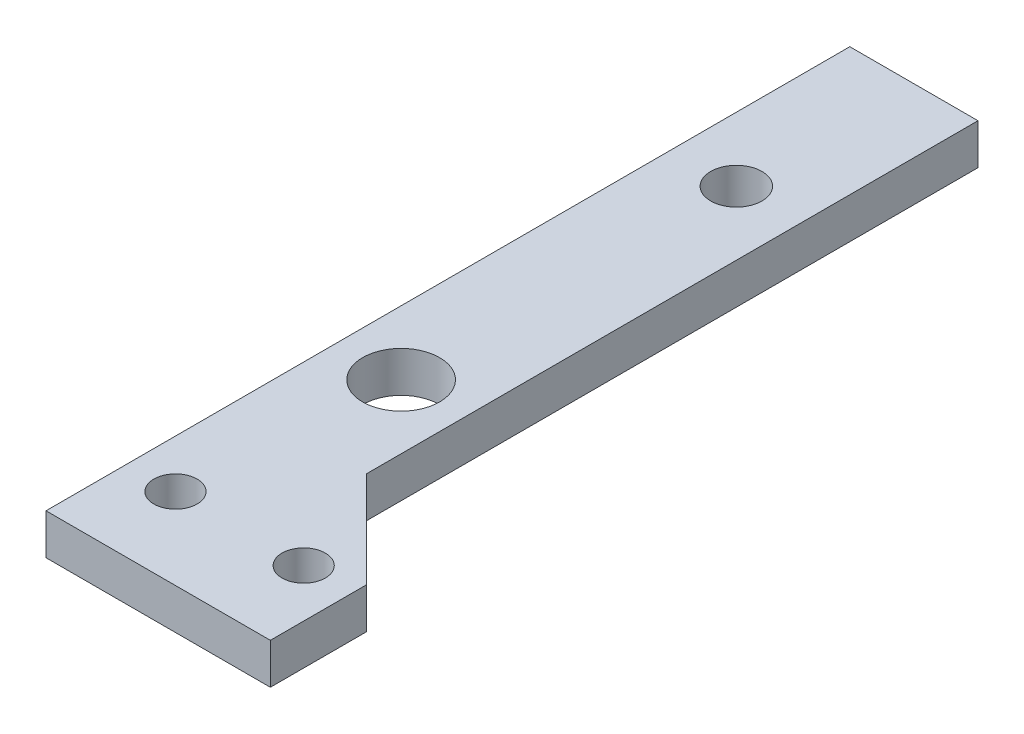
SolidWorks part; units mm, degrees
ref_plane "Front Plane" through (0, 0, 0) normal (0, 0, 1) x (1, 0, 0)
ref_plane "Top Plane" through (0, 0, 0) normal (0, 1, 0) x (1, 0, 0)
ref_plane "Right Plane" through (0, 0, 0) normal (1, 0, 0) x (0, 0, -1)
sketch "Sketch2" plane through (0, 0, 0) normal (0, 1, 0) x (1, 0, 0)
  line L0 (10, 0) -> (10, -100) construction
  line L1 (0, 0) -> (20, 0)
  line L2 (0, 0) -> (0, -100)
  line L3 (0, -100) -> (20, -100)
  line L4 (20, 0) -> (20, -100)
  circle A0 centre (10, -80) radius 6
  circle A1 centre (10, -27.7) radius 4
  dimension "D3" = 8
  dimension "D4" = 12
  dimension "D1" = 100
  dimension "D2" = 20
  dimension "D5" = 52.3
  dimension "D6" = 20
extrude "Boss-Extrude1" add sketch "Sketch2" along normal blind 6.35
sketch "Sketch4" plane through (0, 6.35, 0) normal (0, 1, 0) x (1, 0, 0)
  line L0 (0, -100) -> (20, -100) construction
  line L1 (0, -100) -> (20, -100)
  line L2 (0, -100) -> (0, -125.4)
  line L3 (0, -125.4) -> (20, -125.4)
  line L4 (20, -100) -> (20, -125.4)
  dimension "D1" = 25.4
extrude "Boss-Extrude2" add sketch "Sketch4" against normal up to surface (6.35 mm away) up to face at (10, 0, 50)
sketch "Sketch8" plane through (0, 6.35, 0) normal (0, 1, 0) x (1, 0, 0)
  line L0 (20, -125.4) -> (35, -125.4)
  line L1 (35, -125.4) -> (35, -110.4)
  line L2 (35, -110.4) -> (20, -95.4)
  line L3 (20, -125.4) -> (20, 0) construction
  line L4 (20, -95.4) -> (20, -125.4)
  dimension "D1" = 45
  dimension "D2" = 15
  dimension "D3" = 15
extrude "Boss-Extrude3" add sketch "Sketch8" against normal up to surface (6.35 mm away) up to face at (10, 0, 62.7)
sketch "Sketch5" plane through (0, 6.35, 0) normal (0, 1, 0) x (1, 0, 0)
  line L0 (17.5, -125.4) -> (17.5, -112.7) construction
  line L1 (0, -125.4) -> (35, -125.4) construction
  line L2 (7.5, -112.7) -> (27.5, -112.7) construction
  point P7 (17.5, -112.7)
  dimension "D1" = 12.7
  dimension "D2" = 20
hole_wizard "1/4 Clearance Hole2" positions "Sketch9" profile "Sketch10" hole size "1/4" standard "ANSI Inch" end condition through all
sketch "Sketch9" plane through (0, 6.35, 0) normal (0, 1, 0) x (1, 0, 0)
  point P0 (7.5, -112.7)
  point P3 (27.5, -112.7)
sketch "Sketch10" plane through (7.5, 6.35, 112.7) normal (1, 0, 0) x (0, 0, 1)
  line L0 (0, 0) -> (0, 6.35)
  line L1 (0, 6.35) -> (3.3782, 6.35)
  line L2 (3.3782, 6.35) -> (3.3782, 0)
  line L5 (3.3782, 0) -> (0, 0)
  line L11 (0, -6.35) -> (0, 107.95) construction
  dimension "Thru Hole Dia." = 6.7564
  dimension "Thru Hole Depth" = 6.35
